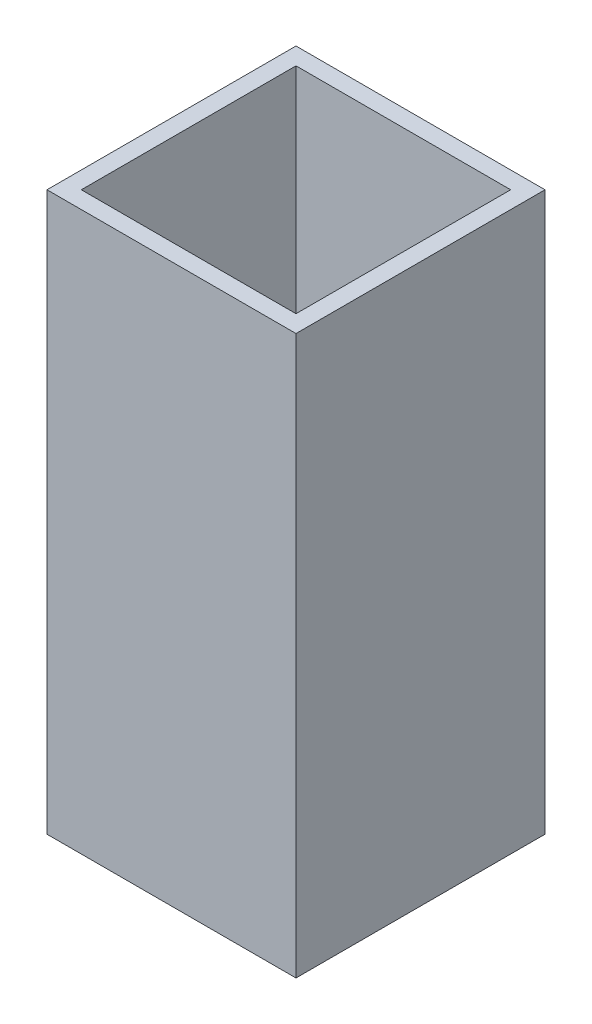
SolidWorks part; units mm, degrees
ref_plane "Спереди" through (0, 0, 0) normal (0, 0, 1) x (1, 0, 0)
ref_plane "Сверху" through (0, 0, 0) normal (0, 1, 0) x (1, 0, 0)
ref_plane "Справа" through (0, 0, 0) normal (1, 0, 0) x (0, 0, -1)
sketch "Эскиз1" plane through (0, 0, 0) normal (0, 1, 0) x (1, 0, 0)
  line L1 (-14.5, -14.5) -> (14.5, -14.5)
  line L2 (-14.5, -14.5) -> (-14.5, 14.5)
  line L3 (-14.5, 14.5) -> (14.5, 14.5)
  line L4 (14.5, -14.5) -> (14.5, 14.5)
  line L5 (-14.5, -14.5) -> (14.5, 14.5) construction
  line L6 (-14.5, 14.5) -> (14.5, -14.5) construction
  point P0 (0, 0)
  dimension "D1" = 29
extrude "Бобышка-Вытянуть1" add sketch "Эскиз1" along normal blind 65
shell "Оболочка1" thickness 2
